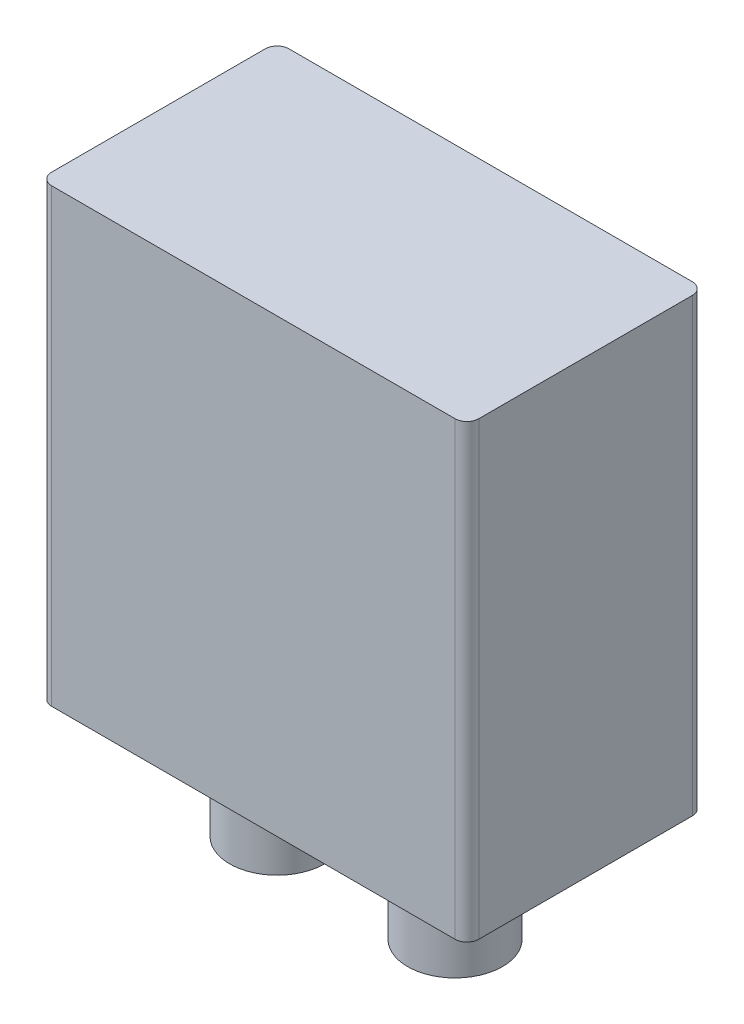
SolidWorks part; units mm, degrees
ref_plane "Front Plane" through (0, 0, 0) normal (0, 0, 1) x (1, 0, 0)
ref_plane "Top Plane" through (0, 0, 0) normal (0, 1, 0) x (1, 0, 0)
ref_plane "Right Plane" through (0, 0, 0) normal (1, 0, 0) x (0, 0, -1)
sketch "Sketch1" plane through (0, 0, 0) normal (0, 0, 1) x (1, 0, 0)
  line L1 (-18, -19) -> (18, -19)
  line L2 (-18, -19) -> (-18, 19)
  line L3 (-18, 19) -> (18, 19)
  line L4 (18, -19) -> (18, 19)
  line L5 (-18, -19) -> (18, 19) construction
  line L6 (-18, 19) -> (18, -19) construction
  point P0 (0, 0)
  dimension "D1" = 36
  dimension "D2" = 38
extrude "Boss-Extrude1" add sketch "Sketch1" along normal blind 20
fillet "Fillet1" radius 1 4 edges at (18, 0, 0) (18, 0, 20) (-18, 0, 0) (-18, 0, 20)
sketch "Sketch2" plane through (0, -19, 0) normal (0, -1, 0) x (1, 0, 0)
  line L0 (-18, 10) -> (18, 10) construction
  line L1 (-18, 19) -> (-18, 1) construction
  line L2 (18, 19) -> (18, 1) construction
  circle A0 centre (-8, 10) radius 4
  circle A1 centre (7, 10) radius 4
  dimension "D1" = 8
  dimension "D2" = 10
  dimension "D3" = 2
extrude "Boss-Extrude2" add sketch "Sketch2" along normal blind 10 separate body
